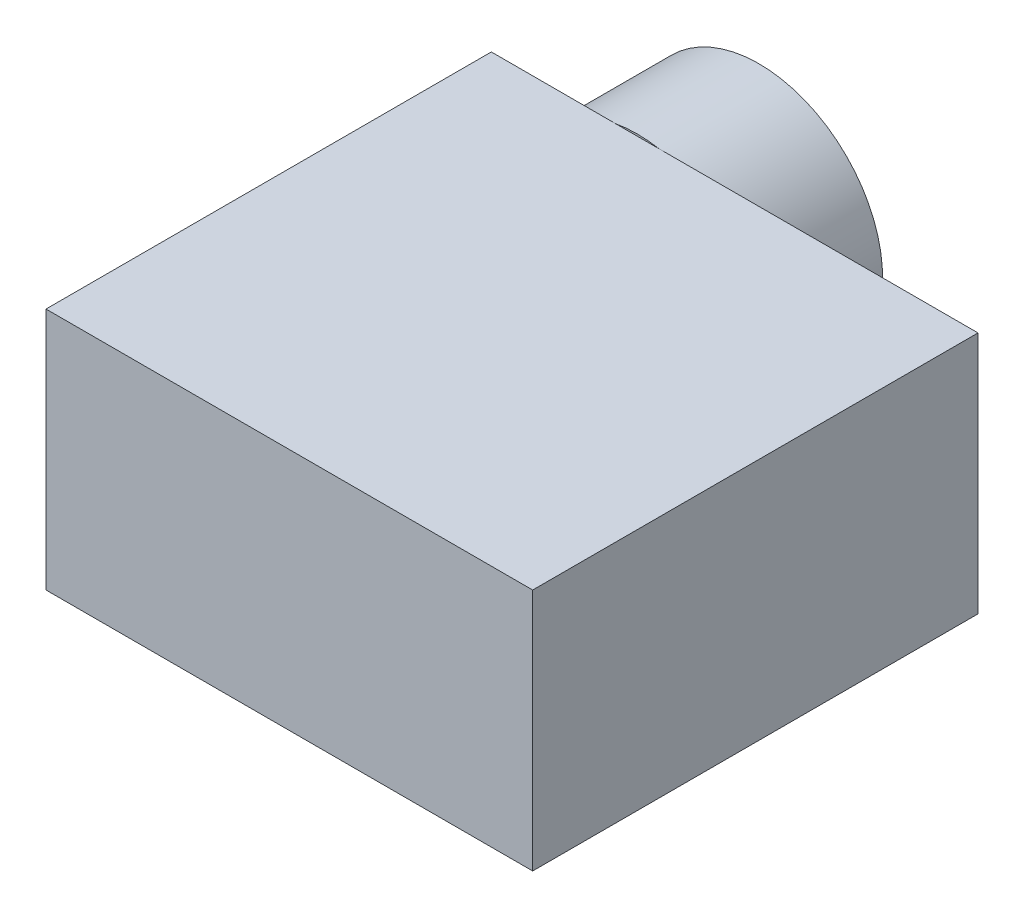
SolidWorks part; units mm, degrees
ref_plane "Front Plane" through (0, 0, 0) normal (0, 0, 1) x (1, 0, 0)
ref_plane "Top Plane" through (0, 0, 0) normal (0, 1, 0) x (1, 0, 0)
ref_plane "Right Plane" through (0, 0, 0) normal (1, 0, 0) x (0, 0, -1)
sketch "Sketch1" plane through (0, 0, 0) normal (0, 1, 0) x (1, 0, 0)
  line L1 (-12, 10) -> (28, 10)
  line L2 (-12, 10) -> (-12, -26.6)
  line L3 (-12, -26.6) -> (28, -26.6)
  line L4 (28, 10) -> (28, -26.6)
  line L5 (-55, 0) -> (55, 0) construction
  line L6 (-12, 0) -> (28, 0) construction
  line L7 (0, 10) -> (0, -26.6) construction
  line L9 (0, -55) -> (0, 55) construction
  dimension "D1" = 40
  dimension "D2" = 36.6
  dimension "D3" = 26.6
  dimension "D4" = 12
extrude "Boss-Extrude1" add sketch "Sketch1" along normal mid plane 20
sketch "Sketch2" plane through (0, 0, -10) normal (0, 0, -1) x (-1, 0, 0)
  circle A0 centre (0, 0) radius 10.16
  dimension "D1" = 20.32
extrude "Boss-Extrude2" add sketch "Sketch2" along normal blind 10
move or copy body "Body-Move/Copy1" [suppressed] bodies to move or copy 102
